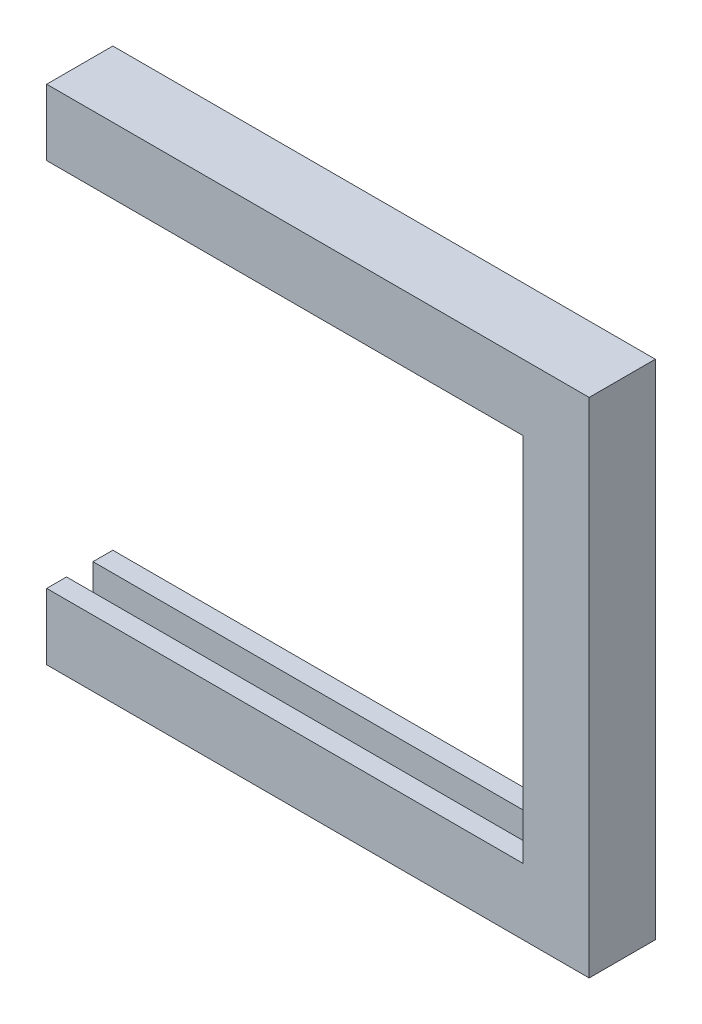
SolidWorks part; units mm, degrees
ref_plane "Plan de face" through (0, 0, 0) normal (0, 0, 1) x (1, 0, 0)
ref_plane "Plan de dessus" through (0, 0, 0) normal (0, 1, 0) x (1, 0, 0)
ref_plane "Plan de droite" through (0, 0, 0) normal (1, 0, 0) x (0, 0, -1)
sketch "Esquisse1" plane through (0, 0, 0) normal (0, 0, 1) x (1, 0, 0)
  line L1 (0, 0) -> (41, 0)
  line L2 (0, 0) -> (0, 38)
  line L3 (0, 38) -> (41, 38)
  line L4 (41, 0) -> (41, 38)
  dimension "D1" = 41
  dimension "D2" = 38
extrude "Boss.-Extru.1" add sketch "Esquisse1" along normal blind 5
sketch "Esquisse6" plane through (0, 0, 0) normal (0, 0, -1) x (-1, 0, 0)
  line L0 (0, 38) -> (0, 0) construction
  line L1 (0, 29.5) -> (-36, 29.5)
  line L2 (0, 29.5) -> (0, 8.5)
  line L3 (0, 8.5) -> (-36, 8.5)
  line L4 (-36, 29.5) -> (-36, 8.5)
  line L5 (-41, 0) -> (-41, 38) construction
  line L6 (0, 19) -> (-41, 19) construction
  point P10 (0, 19)
  dimension "D1" = 21
  dimension "D3" = 5
extrude "Enlèv. mat.-Extru.3" cut sketch "Esquisse6" against normal blind 5
sketch "Esquisse7" plane through (0, 0, 0) normal (-1, 0, 0) x (0, 0, 1)
  line L0 (2.5, 38) -> (2.5, 0) construction
  line L1 (3.5, 3) -> (1.5, 3)
  line L2 (3.5, 3) -> (3.5, 35)
  line L3 (3.5, 35) -> (1.5, 35)
  line L4 (1.5, 3) -> (1.5, 35)
  line L5 (5, 38) -> (0, 38) construction
  line L6 (5, 0) -> (0, 0) construction
  point P4 (2.5, 35)
  dimension "D1" = 3
  dimension "D2" = 3
  dimension "D3" = 2
extrude "Enlèv. mat.-Extru.4" cut sketch "Esquisse7" against normal blind 36
sketch "Esquisse8" plane through (0, 0, 0) normal (-1, 0, 0) x (0, 0, 1)
  line L0 (0, 38) -> (0, 29.5) construction
  line L1 (0, 33) -> (5, 33)
  line L2 (0, 33) -> (0, 5)
  line L3 (0, 5) -> (5, 5)
  line L4 (5, 33) -> (5, 5)
  line L5 (5, 38) -> (5, 29.5) construction
  line L6 (5, 0) -> (0, 0) construction
  dimension "D1" = 28
  dimension "D2" = 5
extrude "Enlèv. mat.-Extru.5" cut sketch "Esquisse8" against normal blind 36
